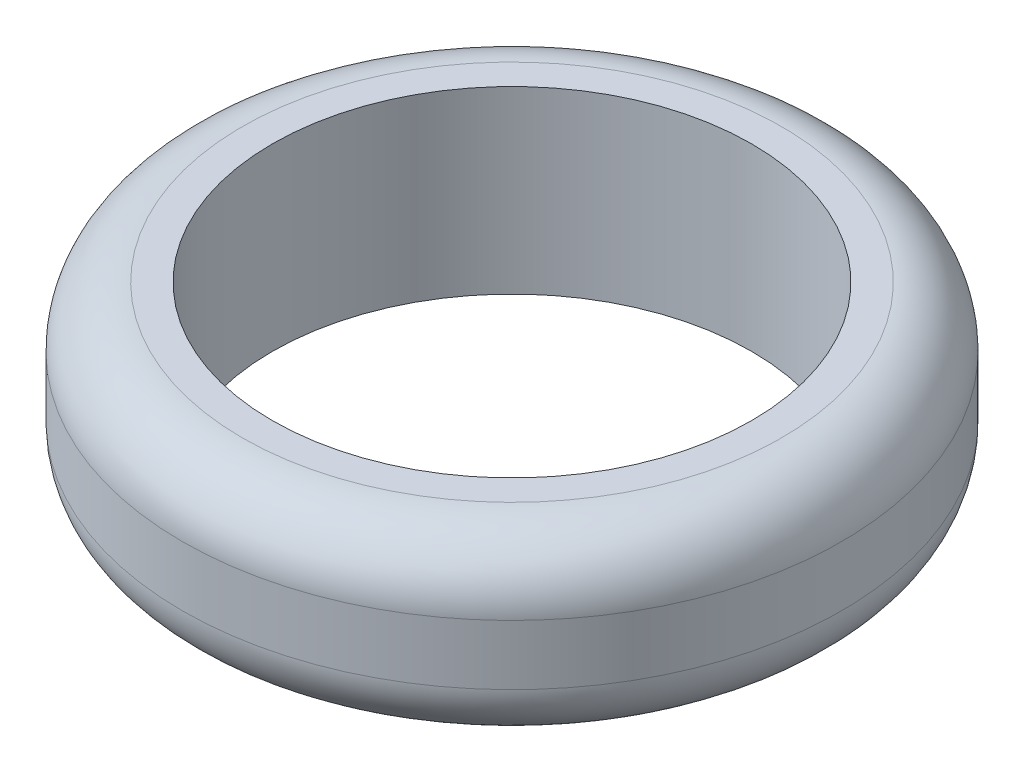
SolidWorks part; units mm, degrees
ref_plane "Alzado" through (0, 0, 0) normal (0, 0, 1) x (1, 0, 0)
ref_plane "Planta" through (0, 0, 0) normal (0, 1, 0) x (1, 0, 0)
ref_plane "Vista lateral" through (0, 0, 0) normal (1, 0, 0) x (0, 0, -1)
sketch "Croquis1" plane through (0, 0, 0) normal (0, 1, 0) x (1, 0, 0)
  circle A0 centre (0, 0) radius 5.5
extrude "Saliente-Extruir1" add sketch "Croquis1" along normal blind 3
sketch "Croquis2" plane through (0, 3, 0) normal (0, 1, 0) x (1, 0, 0)
  circle A0 centre (0, 0) radius 4
extrude "Cortar-Extruir1" cut sketch "Croquis2" against normal blind 5
fillet "Redondeo1" radius 1 1 edges at (0, 3, 5.5)
fillet "Redondeo2" radius 1 1 edges at (0, 0, 5.5)
